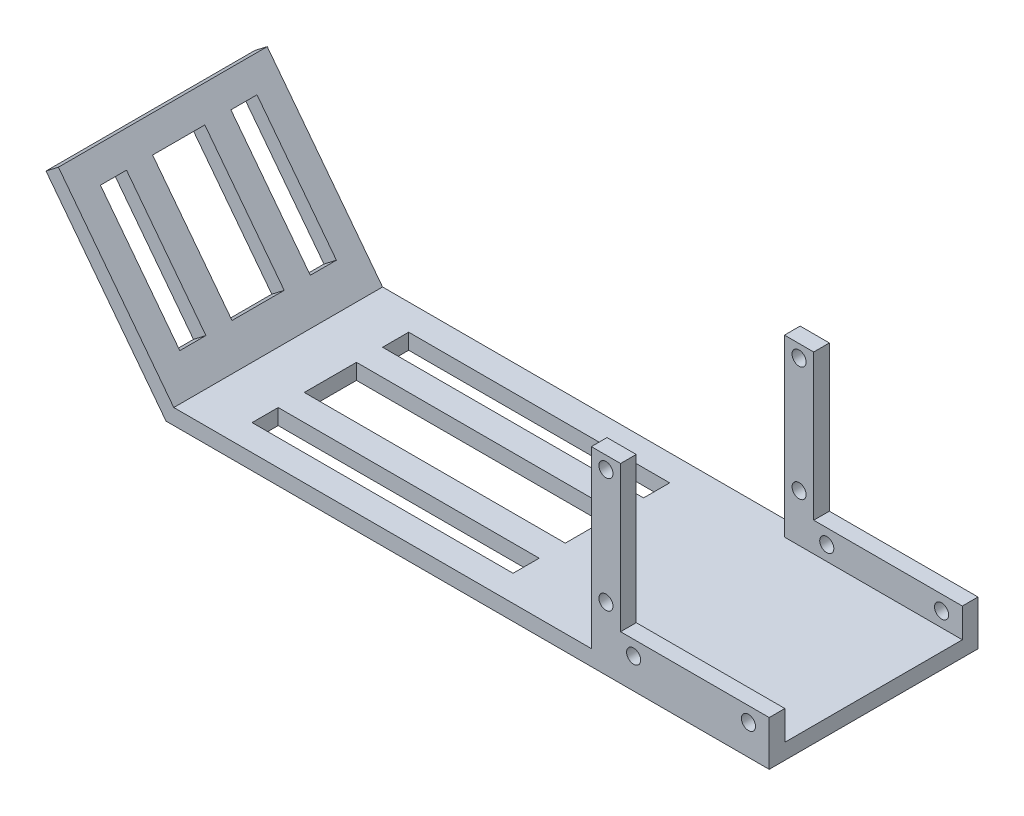
SolidWorks part; units mm, degrees
material "Aluminium 1050"
ref_plane "Front Plane" through (0, 0, 0) normal (0, 0, 1) x (1, 0, 0)
ref_plane "Top Plane" through (0, 0, 0) normal (0, 1, 0) x (1, 0, 0)
ref_plane "Right Plane" through (0, 0, 0) normal (1, 0, 0) x (0, 0, -1)
sketch "Sketch1" plane through (0, 0, 0) normal (0, 0, 1) x (1, 0, 0)
  line L0 (0, 0) -> (-115.55, 0)
  line L1 (0, 3) -> (-114.0698, 3)
  line L2 (0, 0) -> (0, 3)
  line L3 (-115.55, 0) -> (-138.55, 0)
  line L4 (-138.55, 0) -> (-138.55, 30)
  line L5 (-115.55, 0) -> (-138.55, 30)
  line L6 (-138.55, 30) -> (-136.1692, 31.8253)
  line L7 (-136.1692, 31.8253) -> (-114.0698, 3)
  line L8 (-138.55, 30) -> (-115.55, 0)
  line L9 (0, 3) -> (-115.55, 3) construction
  dimension "D1" = 115.55
  dimension "D3" = 23
  dimension "D4" = 30
  dimension "D5" = 3
  dimension "D2" = 3
extrude "Boss-Extrude1" add sketch "Sketch1" along normal blind 34
sketch "Sketch2" plane through (0, 0, 34) normal (0, 0, 1) x (1, 0, 0)
  line L3 (0, 3) -> (-114.0698, 3) construction
  line L4 (-114.0698, 3) -> (-104.0698, 3)
  line L8 (-100.5041, 3) -> (-34.075, 3)
  line L9 (-114.0698, 3) -> (-136.1692, 31.8253)
  line L10 (-136.1692, 31.8253) -> (-138.55, 30)
  line L11 (-138.55, 30) -> (-115.55, 0)
  line L12 (-115.55, 0) -> (0, 0)
  line L13 (0, 0) -> (0, 8.6)
  line L14 (-22.125, 8.6) -> (20.675, 8.6) construction
  line L15 (0, 8.6) -> (-28.475, 8.6)
  line L16 (-28.475, 8.6) -> (-28.475, 36.5121)
  line L18 (-34.075, 36.5121) -> (-34.075, 3)
  line L20 (-34.075, 36.5121) -> (-28.475, 36.5121)
  line L21 (-104.0698, 3) -> (-100.5041, 3)
  circle A0 centre (-3.975, 5.8) radius 1.35
  circle A1 centre (-25.975, 5.8) radius 1.35
  circle A2 centre (-31.275, 34.1) radius 1.35
  circle A3 centre (-31.275, 12.1) radius 1.35
  dimension "D2" = 10
extrude "Boss-Extrude4" add sketch "Sketch2" against normal blind 3 from surface at -34
sketch "Sketch3" plane through (0, 0, 34) normal (0, 0, 1) x (1, 0, 0)
  line L0 (0, 0) -> (0, 3)
  line L2 (-114.0698, 3) -> (-136.1692, 31.8253)
  line L3 (-136.1692, 31.8253) -> (-138.55, 30)
  line L4 (-138.55, 30) -> (-115.55, 0)
  line L5 (-115.55, 0) -> (0, 0)
  line L6 (-114.0698, 3) -> (-34.075, 3)
  line L7 (-34.075, 3) -> (-34.075, 36.5121)
  line L8 (-34.075, 36.5121) -> (-28.475, 36.5121)
  line L9 (-28.475, 36.5121) -> (-28.475, 8.6)
  line L10 (-28.475, 8.6) -> (0, 8.6)
  line L11 (0, 8.6) -> (0, 3)
  circle A0 centre (-31.275, 34.1) radius 1.35
  circle A1 centre (-31.275, 12.1) radius 1.35
  circle A2 centre (-25.975, 5.8) radius 1.35
  circle A3 centre (-3.975, 5.8) radius 1.35
extrude "Boss-Extrude5" add sketch "Sketch3" along normal blind 3
sketch "Sketch4" plane through (0, 3, 0) normal (0, 1, 0) x (1, 0, 0)
  line L0 (-54.0698, -17) -> (-104.0698, -17)
  line L1 (-54.0698, -27) -> (-54.0698, -32)
  line L2 (-104.0698, -27) -> (-104.0698, -32)
  line L3 (-54.0698, -12) -> (-104.0698, -12)
  line L4 (-54.0698, -22) -> (-104.0698, -22)
  line L5 (-54.0698, -7) -> (-104.0698, -7)
  line L6 (-54.0698, -27) -> (-104.0698, -27)
  line L7 (-54.0698, -2) -> (-104.0698, -2)
  line L8 (-54.0698, -32) -> (-104.0698, -32)
  line L9 (-114.0698, 3) -> (-114.0698, -37)
  line L10 (-104.0698, -2) -> (-104.0698, -7)
  line L11 (-54.0698, -2) -> (-54.0698, -7)
  line L12 (-104.0698, 3) -> (-104.0698, -37) construction
  line L13 (0, -2) -> (-114.0698, -2) construction
  line L14 (0, -7) -> (-114.0698, -7) construction
  line L15 (0, -12) -> (-114.0698, -12) construction
  line L16 (0, -17) -> (-114.0698, -17) construction
  line L17 (0, -22) -> (-114.0698, -22) construction
  line L18 (0, -27) -> (-114.0698, -27) construction
  line L19 (0, -32) -> (-114.0698, -32) construction
  line L20 (-54.0698, 3) -> (-54.0698, -37) construction
  line L21 (-104.0698, -12) -> (-104.0698, -22)
  line L22 (-54.0698, -12) -> (-54.0698, -22)
  dimension "D1" = 5
  dimension "D2" = 5
  dimension "D3" = 10
  dimension "D4" = 10
  dimension "D5" = 15
  dimension "D6" = 15
  dimension "D7" = 10
  dimension "D8" = 50
extrude "Cut-Extrude1" cut sketch "Sketch4" against normal up to next contours L11 L7 L10 L5 | L8 L1 L6 L2 | L3 L21 L4 L22
sketch "Sketch5" plane through (-70.3938, -53.9686, 0) normal (0.7936, 0.6084, 0) x (0, 0, -1)
  line L0 (-37, 108.1064) -> (3, 108.1064)
  line L1 (-37, 78.1064) -> (3, 78.1064)
  line L2 (-17, 108.1064) -> (-17, 78.1064)
  line L3 (-22, 108.1064) -> (-22, 78.1064)
  line L4 (-12, 108.1064) -> (-12, 78.1064)
  line L5 (-27, 108.1064) -> (-27, 78.1064)
  line L6 (-7, 108.1064) -> (-7, 78.1064)
  line L7 (-32, 108.1064) -> (-32, 78.1064)
  line L8 (-2, 108.1064) -> (-2, 78.1064)
  line L9 (-37, 108.1064) -> (-37, 78.1064)
  line L10 (3, 108.1064) -> (3, 78.1064)
  line L11 (-37, 103.1064) -> (3, 103.1064)
  dimension "D2" = 5
  dimension "D1" = 30
  dimension "D3" = 5
  dimension "D4" = 10
  dimension "D5" = 10
  dimension "D6" = 15
  dimension "D7" = 15
  dimension "D8" = 5
extrude "Cut-Extrude3" cut sketch "Sketch5" against normal up to next contours L11 L3 L1 L2 | L11 L2 L1 L4 | L11 L6 L1 L8 | L11 L7 L1 L5
